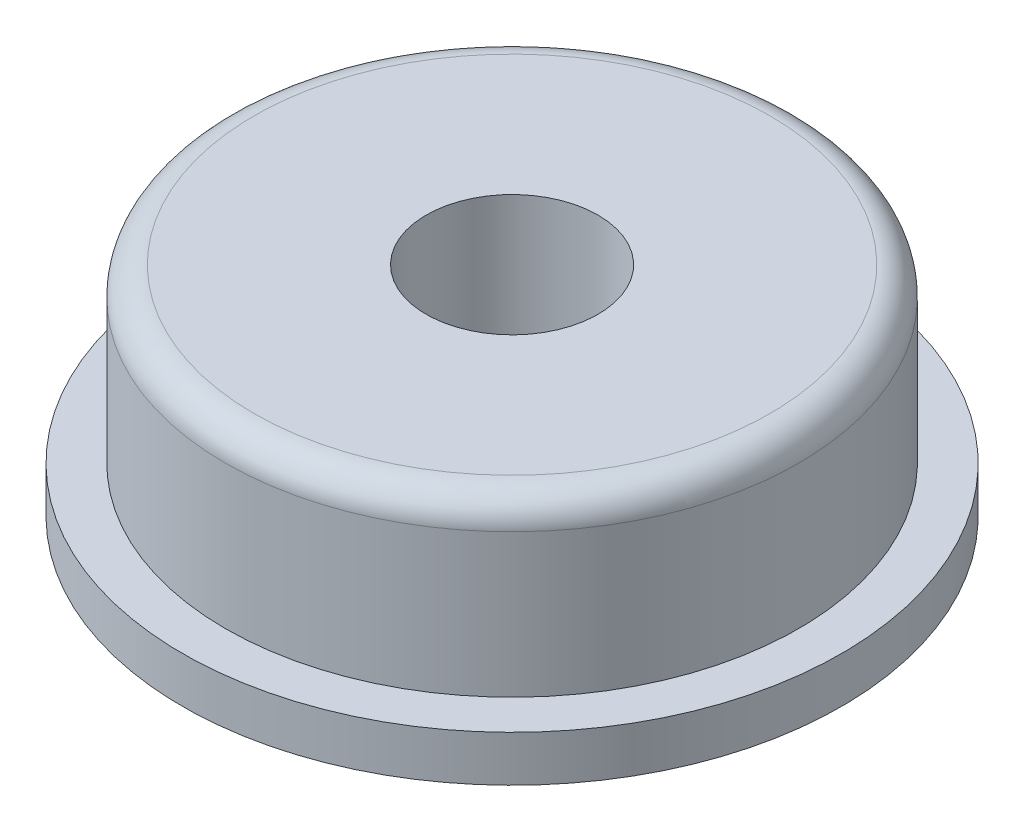
SolidWorks part; units mm, degrees
ref_plane "Front Plane" through (0, 0, 0) normal (0, 0, 1) x (1, 0, 0)
ref_plane "Top Plane" through (0, 0, 0) normal (0, 1, 0) x (1, 0, 0)
ref_plane "Right Plane" through (0, 0, 0) normal (1, 0, 0) x (0, 0, -1)
sketch "Sketch1" plane through (0, 0, 0) normal (0, 1, 0) x (1, 0, 0)
  circle A0 centre (0, 0) radius 5.75
  circle A1 centre (0, 0) radius 1.5
  dimension "D1" = 11.5
  dimension "D2" = 3
extrude "Boss-Extrude1" add sketch "Sketch1" along normal blind 3.8
sketch "Sketch2" plane through (0, 3.8, 0) normal (0, 1, 0) x (1, 0, 0)
  circle A0 centre (0, 0) radius 5
  dimension "D1" = 10
extrude "Cut-Extrude1" cut sketch "Sketch2" against normal blind 3 flip side to cut
fillet "Fillet1" radius 0.5 1 edges at (0, 3.8, 5)
